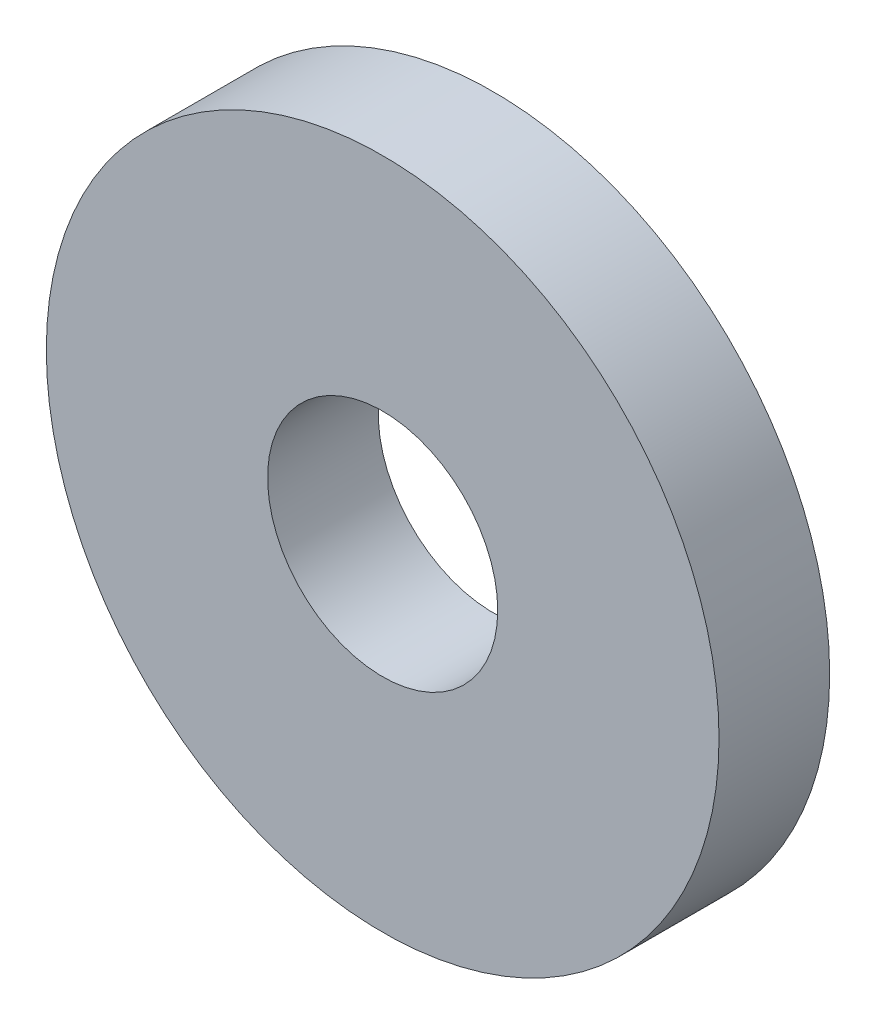
SolidWorks part; units mm, degrees
material "Delrin 2700 NC010, Low Viscosity Acetal Copolymer (SS)"
ref_plane "Front Plane" through (0, 0, 0) normal (0, 0, 1) x (1, 0, 0)
ref_plane "Top Plane" through (0, 0, 0) normal (0, 1, 0) x (1, 0, 0)
ref_plane "Right Plane" through (0, 0, 0) normal (1, 0, 0) x (0, 0, -1)
sketch "Sketch1" plane through (0, 0, 0) normal (0, 0, 1) x (1, 0, 0)
  circle A0 centre (0, 0) radius 3.302
  circle A1 centre (0, 0) radius 9.652
  dimension "D1" = 6.604
  dimension "D2" = 6.35
extrude "Boss-Extrude1" add sketch "Sketch1" along normal blind 3.175
